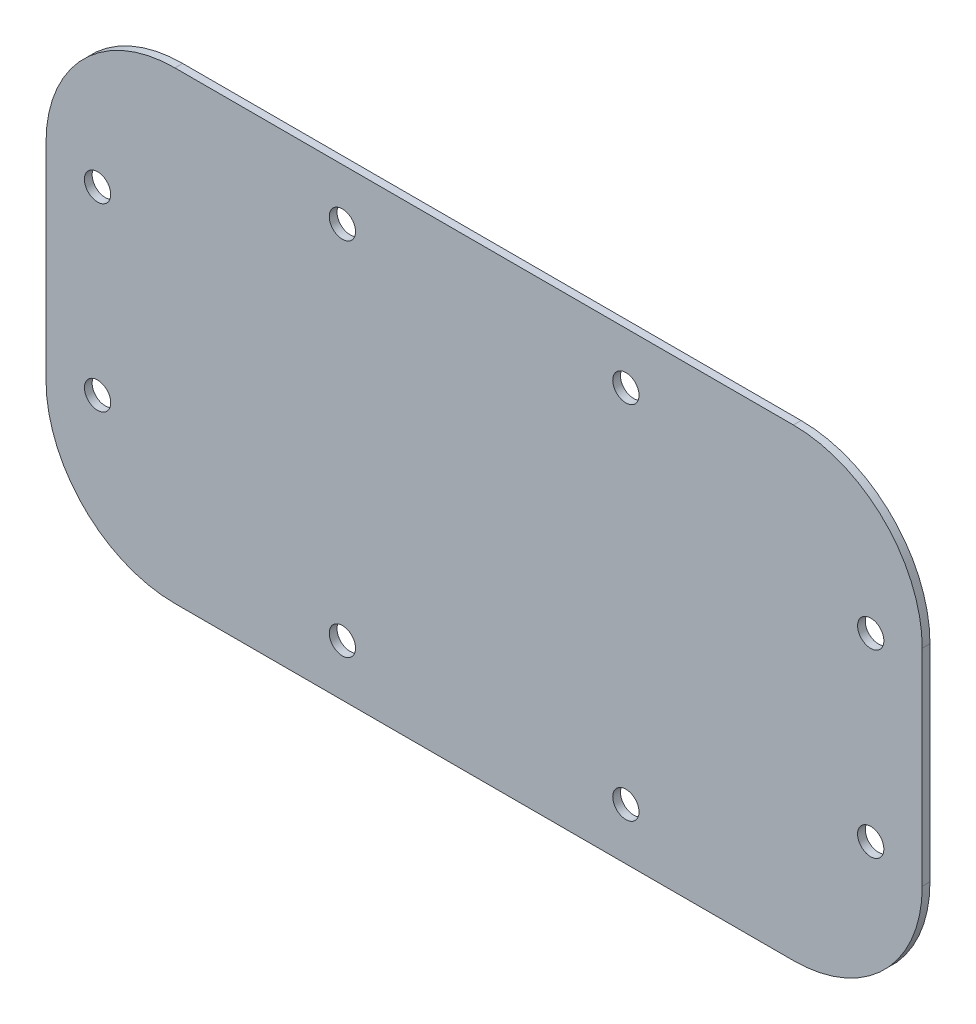
SolidWorks part; units mm, degrees
ref_plane "Płaszczyzna przednia" through (0, 0, 0) normal (0, 0, 1) x (1, 0, 0)
ref_plane "Płaszczyzna górna" through (0, 0, 0) normal (0, 1, 0) x (1, 0, 0)
ref_plane "Płaszczyzna prawa" through (0, 0, 0) normal (1, 0, 0) x (0, 0, -1)
sketch "Szkic1" plane through (0, 0, 0) normal (0, 0, 1) x (1, 0, 0)
  line L1 (-120, -90) -> (120, -90)
  line L2 (-170, -40) -> (-170, 40)
  line L3 (-120, 90) -> (120, 90)
  line L4 (170, -40) -> (170, 40)
  line L5 (-170, -90) -> (170, 90) construction
  line L6 (-170, 90) -> (170, -90) construction
  arc A0 (-120, -90) -> (-170, -40) centre (-120, -40) cw
  arc A1 (120, -90) -> (170, -40) centre (120, -40) ccw
  arc A2 (120, 90) -> (170, 40) centre (120, 40) cw
  arc A3 (-170, 40) -> (-120, 90) centre (-120, 40) cw
  point P0 (0, 0)
  dimension "D1" = 50
  dimension "D2" = 340
  dimension "D3" = 180
extrude "Dodanie-wyciągnięcie1" add sketch "Szkic1" along normal blind 3
hole_wizard "Otwór gwintowany M121" positions "Szkic2" profile "Szkic3" tap size "M12" standard "ISO" end condition through all
sketch "Szkic2" plane through (0, 0, 0) normal (0, 0, -1) x (-1, 0, 0)
  line L0 (0, 0) -> (0, -62.2789) construction
  line L2 (0, 0) -> (-132.7414, 0) construction
  point P0 (55, 70)
  point P2 (-55, 70)
  point P4 (55, -70)
  point P6 (-55, -70)
  point P8 (-150, 35)
  point P10 (-150, -35)
  point P12 (150, -35)
  point P14 (150, 35)
  dimension "D1" = 55
  dimension "D2" = 55
  dimension "D3" = 35
  dimension "D4" = 35
  dimension "D5" = 150
  dimension "D6" = 150
  dimension "D7" = 70
  dimension "D8" = 70
sketch "Szkic3" plane through (-55, 70, 0) normal (1, 0, 0) x (0, 1, 0)
  line L0 (0, 0) -> (0, 3)
  line L1 (0, 3) -> (5.1, 3)
  line L2 (5.1, 3) -> (5.1, 0)
  line L5 (5.1, 0) -> (0, 0)
  line L11 (0, -6.35) -> (0, 107.95) construction
  dimension "Średnica zewnętrzna gwintu" = 10.2
  dimension "Głębokość otworu gwintowanego na wylot" = 3
